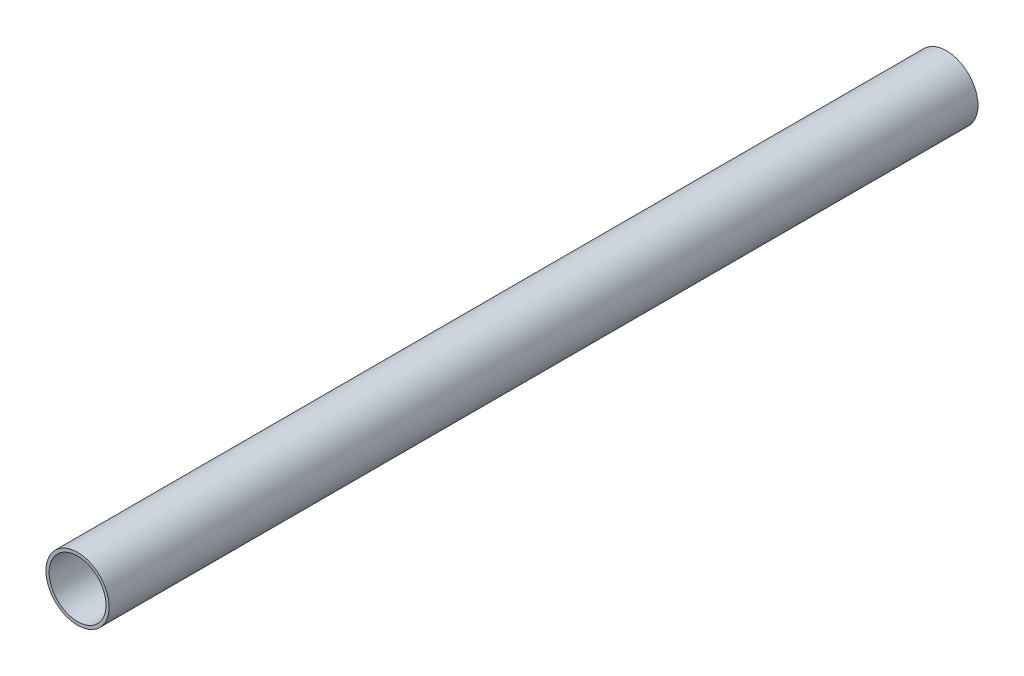
SolidWorks part; units mm, degrees
other "Defeature"
material "6061 Alloy"
ref_plane "Front Plane" through (0, 0, 0) normal (0, 0, 1) x (1, 0, 0)
ref_plane "Top Plane" through (0, 0, 0) normal (0, 1, 0) x (1, 0, 0)
ref_plane "Right Plane" through (0, 0, 0) normal (1, 0, 0) x (0, 0, -1)
sketch "Sketch1" plane through (0, 0, 0) normal (0, 0, 1) x (1, 0, 0)
  circle A0 centre (0, 0) radius 8
  circle A1 centre (0, 0) radius 7.2
  dimension "D1" = 16
  dimension "D2" = 0.8
extrude "Boss-Extrude1" add sketch "Sketch1" along normal mid plane 220
